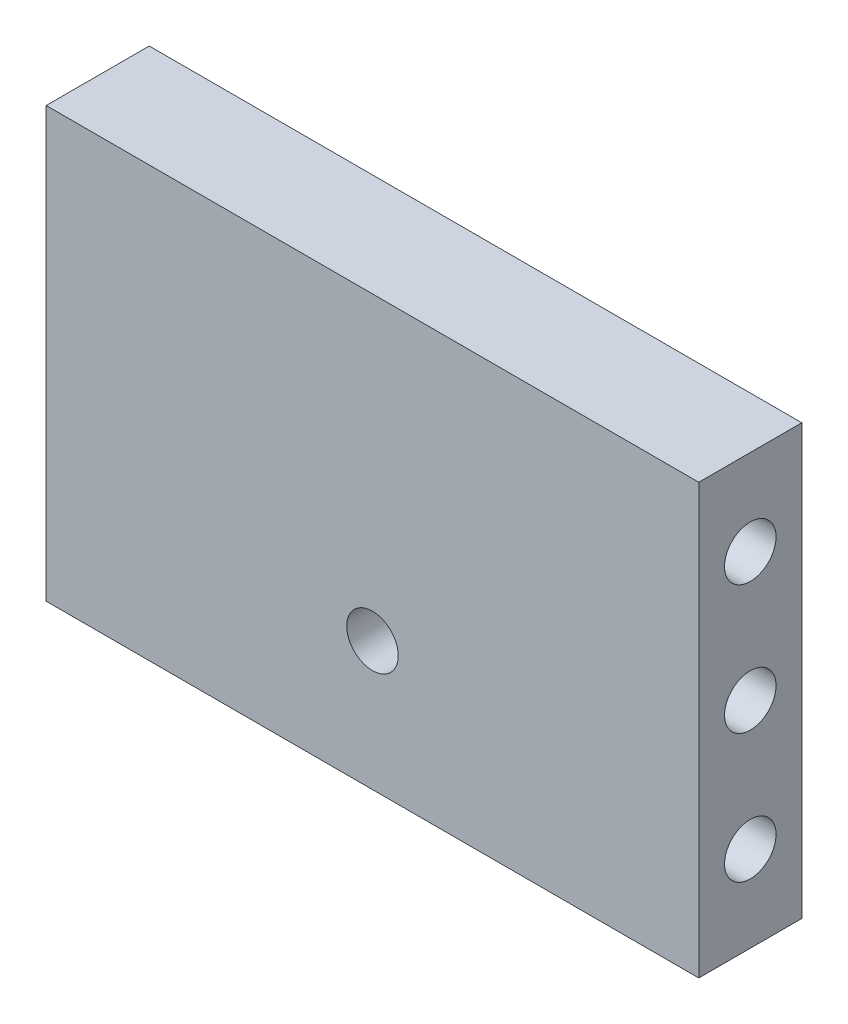
SolidWorks part; units mm, degrees
ref_plane "前视基准面" through (0, 0, 0) normal (0, 0, 1) x (1, 0, 0)
ref_plane "上视基准面" through (0, 0, 0) normal (0, 1, 0) x (1, 0, 0)
ref_plane "右视基准面" through (0, 0, 0) normal (1, 0, 0) x (0, 0, -1)
sketch "草图1" plane through (0, 0, 0) normal (0, 0, 1) x (1, 0, 0)
  line L1 (-38, -25) -> (38, -25)
  line L2 (-38, -25) -> (-38, 25)
  line L3 (-38, 25) -> (38, 25)
  line L4 (38, -25) -> (38, 25)
  line L5 (-38, -25) -> (38, 25) construction
  line L6 (-38, 25) -> (38, -25) construction
  point P0 (0, 0)
  dimension "D1" = 76
  dimension "D2" = 50
extrude "凸台-拉伸1" add sketch "草图1" along normal blind 12
sketch "草图2" plane through (-38, 0, 0) normal (-1, 0, 0) x (0, 0, 1)
  line L0 (0, 25) -> (0, -25) construction
  line L1 (12, -25) -> (0, -25) construction
  circle A0 centre (6, -15) radius 3
  circle A1 centre (6, 0) radius 3
  circle A2 centre (6, 15) radius 3
  dimension "D1" = 6
  dimension "D2" = 6
  dimension "D3" = 10
  dimension "D4" = 3
extrude "切除-拉伸1" cut sketch "草图2" against normal blind 10
sketch "草图3" plane through (38, 0, 0) normal (1, 0, 0) x (0, 0, -1)
  line L0 (0, -25) -> (0, 25) construction
  line L1 (-12, -25) -> (0, -25) construction
  circle A0 centre (-6, -15) radius 3
  circle A1 centre (-6, 0) radius 3
  circle A2 centre (-6, 15) radius 3
  dimension "D1" = 6
  dimension "D2" = 6
  dimension "D3" = 10
  dimension "D4" = 3
extrude "切除-拉伸2" cut sketch "草图3" against normal blind 10
sketch "草图4" plane through (0, -25, 0) normal (0, -1, 0) x (1, 0, 0)
  line L0 (38, 12) -> (38, 0) construction
  line L1 (-38, 0) -> (38, 0) construction
  circle A0 centre (22.5, 6) radius 3
  circle A1 centre (7.5, 6) radius 3
  circle A2 centre (-7.5, 6) radius 3
  circle A3 centre (-22.5, 6) radius 3
  dimension "D1" = 15.5
  dimension "D3" = 6
  dimension "D2" = 6
  dimension "D4" = 4
extrude "切除-拉伸3" cut sketch "草图4" against normal blind 10
sketch "草图5" plane through (0, 0, 0) normal (0, 0, -1) x (-1, 0, 0)
  line L0 (-38, 25) -> (38, 25) construction
  circle A0 centre (0, -10) radius 3
  dimension "D1" = 6
  dimension "D2" = 35
extrude "切除-拉伸4" cut sketch "草图5" against normal blind 12
